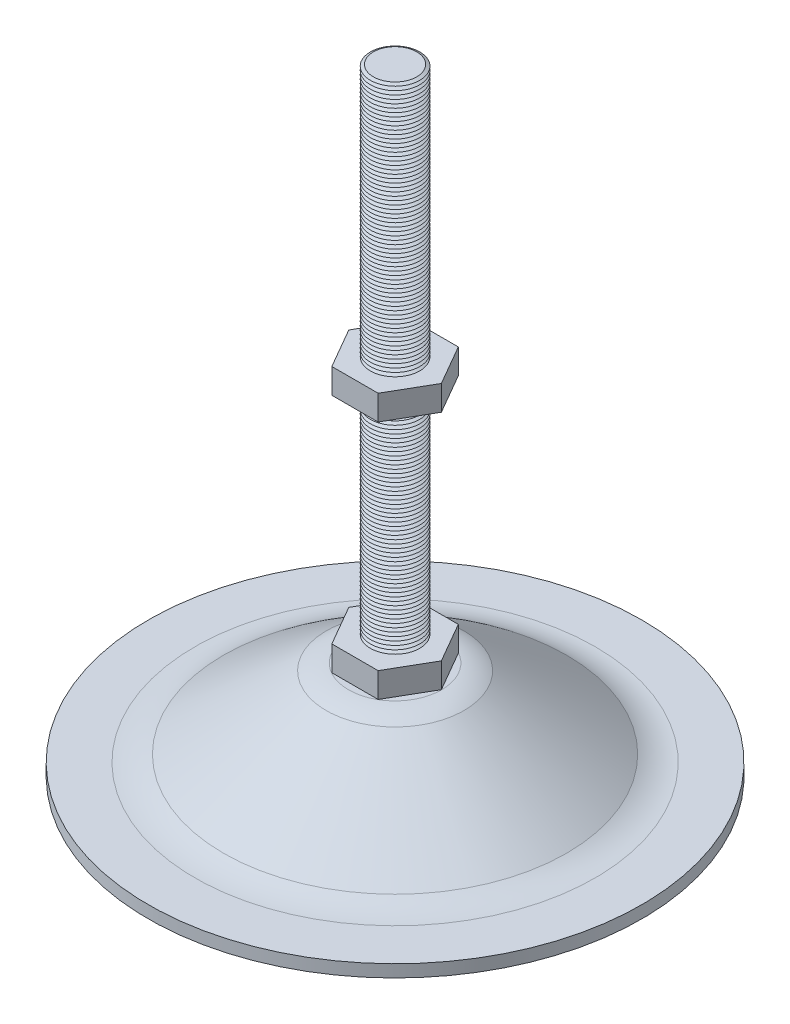
SolidWorks part; units mm, degrees
ref_plane "前视基准面" through (0, 0, 0) normal (0, 0, 1) x (1, 0, 0)
ref_plane "上视基准面" through (0, 0, 0) normal (0, 1, 0) x (1, 0, 0)
ref_plane "右视基准面" through (0, 0, 0) normal (1, 0, 0) x (0, 0, -1)
sketch "草图1" plane through (0, 0, 0) normal (0, 0, 1) x (1, 0, 0)
  line B0 (40, -12) -> (40, -14)
  line B1 (40, -12) -> (32.4605, -12)
  line B2 (27.8204, -10.8583) -> (11.1796, 0.8583)
  line B3 (26.8924, -12.63) -> (10.2516, -0.9133)
  line B4 (6.5395, 0) -> (0, 0)
  line B5 (32.4605, -14) -> (40, -14)
  line B6 (0, 0) -> (0, 86)
  line B7 (7.5, 1.9538) -> (7.5, 6)
  line B8 (4, 6) -> (7.5, 6)
  line B9 (3.5128, 86) -> (0, 86)
  line B10 (7.5, 40.9032) -> (7.5, 44.9495)
  line B11 (3.9956, 44.9495) -> (7.5, 44.9495)
  line B12 (7.5, 40.9032) -> (3.4497, 40.9032)
  line B13 (4, 6) -> (3.4, 6.3091)
  line B14 (4, 6.6182) -> (3.4, 6.3091)
  line B15 (4, 6.6182) -> (3.4, 6.9273)
  line B16 (4, 7.2364) -> (3.4, 6.9273)
  line B17 (4, 7.2364) -> (3.4, 7.5455)
  line B18 (4, 7.8546) -> (3.4, 7.5455)
  line B19 (4, 7.8546) -> (3.4, 8.1637)
  line B20 (4, 8.4728) -> (3.4, 8.1637)
  line B21 (4, 8.4728) -> (3.4, 8.7819)
  line B22 (4, 9.091) -> (3.4, 8.7819)
  line B23 (4, 9.091) -> (3.4, 9.4002)
  line B24 (4, 9.7093) -> (3.4, 9.4002)
  line B25 (4, 9.7093) -> (3.4, 10.0184)
  line B26 (4, 10.3275) -> (3.4, 10.0184)
  line B27 (4, 10.3275) -> (3.4, 10.6366)
  line B28 (4, 10.9457) -> (3.4, 10.6366)
  line B29 (4, 10.9457) -> (3.4, 11.2548)
  line B30 (4, 11.5639) -> (3.4, 11.2548)
  line B31 (4, 11.5639) -> (3.4, 11.873)
  line B32 (4, 12.1821) -> (3.4, 11.873)
  line B33 (4, 12.1821) -> (3.4, 12.4912)
  line B34 (4, 12.8003) -> (3.4, 12.4912)
  line B35 (4, 12.8003) -> (3.4, 13.1094)
  line B36 (4, 13.4185) -> (3.4, 13.1094)
  line B37 (4, 13.4185) -> (3.4, 13.7276)
  line B38 (4, 14.0367) -> (3.4, 13.7276)
  line B39 (4, 14.0367) -> (3.4, 14.3458)
  line B40 (4, 14.6549) -> (3.4, 14.3458)
  line B41 (4, 14.6549) -> (3.4, 14.964)
  line B42 (4, 15.2731) -> (3.4, 14.964)
  line B43 (4, 15.2731) -> (3.4, 15.5822)
  line B44 (4, 15.8913) -> (3.4, 15.5822)
  line B45 (4, 15.8913) -> (3.4, 16.2005)
  line B46 (4, 16.5096) -> (3.4, 16.2005)
  line B47 (4, 16.5096) -> (3.4, 16.8187)
  line B48 (4, 17.1278) -> (3.4, 16.8187)
  line B49 (4, 17.1278) -> (3.4, 17.4369)
  line B50 (4, 17.746) -> (3.4, 17.4369)
  line B51 (4, 17.746) -> (3.4, 18.0551)
  line B52 (4, 18.3642) -> (3.4, 18.0551)
  line B53 (4, 18.3642) -> (3.4, 18.6733)
  line B54 (4, 18.9824) -> (3.4, 18.6733)
  line B55 (4, 18.9824) -> (3.4, 19.2915)
  line B56 (4, 19.6006) -> (3.4, 19.2915)
  line B57 (4, 19.6006) -> (3.4, 19.9097)
  line B58 (4, 20.2188) -> (3.4, 19.9097)
  line B59 (4, 20.2188) -> (3.4, 20.5279)
  line B60 (4, 20.837) -> (3.4, 20.5279)
  line B61 (4, 20.837) -> (3.4, 21.1461)
  line B62 (4, 21.4552) -> (3.4, 21.1461)
  line B63 (4, 21.4552) -> (3.4, 21.7643)
  line B64 (4, 22.0734) -> (3.4, 21.7643)
  line B65 (4, 22.0734) -> (3.4, 22.3825)
  line B66 (4, 22.6916) -> (3.4, 22.3825)
  line B67 (4, 22.6916) -> (3.4, 23.0008)
  line B68 (4, 23.3099) -> (3.4, 23.0008)
  line B69 (4, 23.3099) -> (3.4, 23.619)
  line B70 (4, 23.9281) -> (3.4, 23.619)
  line B71 (4, 23.9281) -> (3.4, 24.2372)
  line B72 (4, 24.5463) -> (3.4, 24.2372)
  line B73 (4, 24.5463) -> (3.4, 24.8554)
  line B74 (4, 25.1645) -> (3.4, 24.8554)
  line B75 (4, 25.1645) -> (3.4, 25.4736)
  line B76 (4, 25.7827) -> (3.4, 25.4736)
  line B77 (4, 25.7827) -> (3.4, 26.0918)
  line B78 (4, 26.4009) -> (3.4, 26.0918)
  line B79 (4, 26.4009) -> (3.4, 26.71)
  line B80 (4, 27.0191) -> (3.4, 26.71)
  line B81 (4, 27.0191) -> (3.4, 27.3282)
  line B82 (4, 27.6373) -> (3.4, 27.3282)
  line B83 (4, 27.6373) -> (3.4, 27.9464)
  line B84 (4, 28.2555) -> (3.4, 27.9464)
  line B85 (4, 28.2555) -> (3.4, 28.5646)
  line B86 (4, 28.8737) -> (3.4, 28.5646)
  line B87 (4, 28.8737) -> (3.4, 29.1828)
  line B88 (4, 29.492) -> (3.4, 29.1828)
  line B89 (4, 29.492) -> (3.4, 29.8011)
  line B90 (4, 30.1102) -> (3.4, 29.8011)
  line B91 (4, 30.1102) -> (3.4, 30.4193)
  line B92 (4, 30.7284) -> (3.4, 30.4193)
  line B93 (4, 30.7284) -> (3.4, 31.0375)
  line B94 (4, 31.3466) -> (3.4, 31.0375)
  line B95 (4, 31.3466) -> (3.4, 31.6557)
  line B96 (4, 31.9648) -> (3.4, 31.6557)
  line B97 (4, 31.9648) -> (3.4, 32.2739)
  line B98 (4, 32.583) -> (3.4, 32.2739)
  line B99 (4, 32.583) -> (3.4, 32.8921)
  line B100 (4, 33.2012) -> (3.4, 32.8921)
  line B101 (4, 33.2012) -> (3.4, 33.5103)
  line B102 (4, 33.8194) -> (3.4, 33.5103)
  line B103 (4, 33.8194) -> (3.4, 34.1285)
  line B104 (4, 34.4376) -> (3.4, 34.1285)
  line B105 (4, 34.4376) -> (3.4, 34.7467)
  line B106 (4, 35.0558) -> (3.4, 34.7467)
  line B107 (4, 35.0558) -> (3.4, 35.3649)
  line B108 (4, 35.674) -> (3.4, 35.3649)
  line B109 (4, 35.674) -> (3.4, 35.9831)
  line B110 (4, 36.2923) -> (3.4, 35.9831)
  line B111 (4, 36.2923) -> (3.4, 36.6014)
  line B112 (4, 36.9105) -> (3.4, 36.6014)
  line B113 (4, 36.9105) -> (3.4, 37.2196)
  line B114 (4, 37.5287) -> (3.4, 37.2196)
  line B115 (4, 37.5287) -> (3.4, 37.8378)
  line B116 (4, 38.1469) -> (3.4, 37.8378)
  line B117 (4, 38.1469) -> (3.4, 38.456)
  line B118 (4, 38.7651) -> (3.4, 38.456)
  line B119 (4, 38.7651) -> (3.4, 39.0742)
  line B120 (4, 39.3833) -> (3.4, 39.0742)
  line B121 (4, 39.3833) -> (3.4, 39.6924)
  line B122 (4, 40.0015) -> (3.4, 39.6924)
  line B123 (4, 40.0015) -> (3.4, 40.3106)
  line B124 (4, 40.6197) -> (3.4, 40.3106)
  line B125 (4, 40.6197) -> (3.4497, 40.9032)
  line B126 (3.9956, 44.9495) -> (3.4, 45.2563)
  line B127 (4, 45.5654) -> (3.4, 45.2563)
  line B128 (4, 45.5654) -> (3.4, 45.8745)
  line B129 (4, 46.1836) -> (3.4, 45.8745)
  line B130 (4, 46.1836) -> (3.4, 46.4927)
  line B131 (4, 46.8018) -> (3.4, 46.4927)
  line B132 (4, 46.8018) -> (3.4, 47.1109)
  line B133 (4, 47.42) -> (3.4, 47.1109)
  line B134 (4, 47.42) -> (3.4, 47.7291)
  line B135 (4, 48.0382) -> (3.4, 47.7291)
  line B136 (4, 48.0382) -> (3.4, 48.3473)
  line B137 (4, 48.6564) -> (3.4, 48.3473)
  line B138 (4, 48.6564) -> (3.4, 48.9655)
  line B139 (4, 49.2746) -> (3.4, 48.9655)
  line B140 (4, 49.2746) -> (3.4, 49.5838)
  line B141 (4, 49.8929) -> (3.4, 49.5838)
  line B142 (4, 49.8929) -> (3.4, 50.202)
  line B143 (4, 50.5111) -> (3.4, 50.202)
  line B144 (4, 50.5111) -> (3.4, 50.8202)
  line B145 (4, 51.1293) -> (3.4, 50.8202)
  line B146 (4, 51.1293) -> (3.4, 51.4384)
  line B147 (4, 51.7475) -> (3.4, 51.4384)
  line B148 (4, 51.7475) -> (3.4, 52.0566)
  line B149 (4, 52.3657) -> (3.4, 52.0566)
  line B150 (4, 52.3657) -> (3.4, 52.6748)
  line B151 (4, 52.9839) -> (3.4, 52.6748)
  line B152 (4, 52.9839) -> (3.4, 53.293)
  line B153 (4, 53.6021) -> (3.4, 53.293)
  line B154 (4, 53.6021) -> (3.4, 53.9112)
  line B155 (4, 54.2203) -> (3.4, 53.9112)
  line B156 (4, 54.2203) -> (3.4, 54.5294)
  line B157 (4, 54.8385) -> (3.4, 54.5294)
  line B158 (4, 54.8385) -> (3.4, 55.1476)
  line B159 (4, 55.4567) -> (3.4, 55.1476)
  line B160 (4, 55.4567) -> (3.4, 55.7658)
  line B161 (4, 56.0749) -> (3.4, 55.7658)
  line B162 (4, 56.0749) -> (3.4, 56.3841)
  line B163 (4, 56.6932) -> (3.4, 56.3841)
  line B164 (4, 56.6932) -> (3.4, 57.0023)
  line B165 (4, 57.3114) -> (3.4, 57.0023)
  line B166 (4, 57.3114) -> (3.4, 57.6205)
  line B167 (4, 57.9296) -> (3.4, 57.6205)
  line B168 (4, 57.9296) -> (3.4, 58.2387)
  line B169 (4, 58.5478) -> (3.4, 58.2387)
  line B170 (4, 58.5478) -> (3.4, 58.8569)
  line B171 (4, 59.166) -> (3.4, 58.8569)
  line B172 (4, 59.166) -> (3.4, 59.4751)
  line B173 (4, 59.7842) -> (3.4, 59.4751)
  line B174 (4, 59.7842) -> (3.4, 60.0933)
  line B175 (4, 60.4024) -> (3.4, 60.0933)
  line B176 (4, 60.4024) -> (3.4, 60.7115)
  line B177 (4, 61.0206) -> (3.4, 60.7115)
  line B178 (4, 61.0206) -> (3.4, 61.3297)
  line B179 (4, 61.6388) -> (3.4, 61.3297)
  line B180 (4, 61.6388) -> (3.4, 61.9479)
  line B181 (4, 62.257) -> (3.4, 61.9479)
  line B182 (4, 62.257) -> (3.4, 62.5661)
  line B183 (4, 62.8752) -> (3.4, 62.5661)
  line B184 (4, 62.8752) -> (3.4, 63.1844)
  line B185 (4, 63.4935) -> (3.4, 63.1844)
  line B186 (4, 63.4935) -> (3.4, 63.8026)
  line B187 (4, 64.1117) -> (3.4, 63.8026)
  line B188 (4, 64.1117) -> (3.4, 64.4208)
  line B189 (4, 64.7299) -> (3.4, 64.4208)
  line B190 (4, 64.7299) -> (3.4, 65.039)
  line B191 (4, 65.3481) -> (3.4, 65.039)
  line B192 (4, 65.3481) -> (3.4, 65.6572)
  line B193 (4, 65.9663) -> (3.4, 65.6572)
  line B194 (4, 65.9663) -> (3.4, 66.2754)
  line B195 (4, 66.5845) -> (3.4, 66.2754)
  line B196 (4, 66.5845) -> (3.4, 66.8936)
  line B197 (4, 67.2027) -> (3.4, 66.8936)
  line B198 (4, 67.2027) -> (3.4, 67.5118)
  line B199 (4, 67.8209) -> (3.4, 67.5118)
  line B200 (4, 67.8209) -> (3.4, 68.13)
  line B201 (4, 68.4391) -> (3.4, 68.13)
  line B202 (4, 68.4391) -> (3.4, 68.7482)
  line B203 (4, 69.0573) -> (3.4, 68.7482)
  line B204 (4, 69.0573) -> (3.4, 69.3664)
  line B205 (4, 69.6756) -> (3.4, 69.3664)
  line B206 (4, 69.6756) -> (3.4, 69.9847)
  line B207 (4, 70.2938) -> (3.4, 69.9847)
  line B208 (4, 70.2938) -> (3.4, 70.6029)
  line B209 (4, 70.912) -> (3.4, 70.6029)
  line B210 (4, 70.912) -> (3.4, 71.2211)
  line B211 (4, 71.5302) -> (3.4, 71.2211)
  line B212 (4, 71.5302) -> (3.4, 71.8393)
  line B213 (4, 72.1484) -> (3.4, 71.8393)
  line B214 (4, 72.1484) -> (3.4, 72.4575)
  line B215 (4, 72.7666) -> (3.4, 72.4575)
  line B216 (4, 72.7666) -> (3.4, 73.0757)
  line B217 (4, 73.3848) -> (3.4, 73.0757)
  line B218 (4, 73.3848) -> (3.4, 73.6939)
  line B219 (4, 74.003) -> (3.4, 73.6939)
  line B220 (4, 74.003) -> (3.4, 74.3121)
  line B221 (4, 74.6212) -> (3.4, 74.3121)
  line B222 (4, 74.6212) -> (3.4, 74.9303)
  line B223 (4, 75.2394) -> (3.4, 74.9303)
  line B224 (4, 75.2394) -> (3.4, 75.5485)
  line B225 (4, 75.8576) -> (3.4, 75.5485)
  line B226 (4, 75.8576) -> (3.4, 76.1667)
  line B227 (4, 76.4759) -> (3.4, 76.1667)
  line B228 (4, 76.4759) -> (3.4, 76.785)
  line B229 (4, 77.0941) -> (3.4, 76.785)
  line B230 (4, 77.0941) -> (3.4, 77.4032)
  line B231 (4, 77.7123) -> (3.4, 77.4032)
  line B232 (4, 77.7123) -> (3.4, 78.0214)
  line B233 (4, 78.3305) -> (3.4, 78.0214)
  line B234 (4, 78.3305) -> (3.4, 78.6396)
  line B235 (4, 78.9487) -> (3.4, 78.6396)
  line B236 (4, 78.9487) -> (3.4, 79.2578)
  line B237 (4, 79.5669) -> (3.4, 79.2578)
  line B238 (4, 79.5669) -> (3.4, 79.876)
  line B239 (4, 80.1851) -> (3.4, 79.876)
  line B240 (4, 80.1851) -> (3.4, 80.4942)
  line B241 (4, 80.8033) -> (3.4, 80.4942)
  line B242 (4, 80.8033) -> (3.4, 81.1124)
  line B243 (4, 81.4215) -> (3.4, 81.1124)
  line B244 (4, 81.4215) -> (3.4, 81.7306)
  line B245 (4, 82.0397) -> (3.4, 81.7306)
  line B246 (4, 82.0397) -> (3.4, 82.3488)
  line B247 (4, 82.6579) -> (3.4, 82.3488)
  line B248 (4, 82.6579) -> (3.4, 82.967)
  line B249 (4, 83.2762) -> (3.4, 82.967)
  line B250 (4, 83.2762) -> (3.4, 83.5853)
  line B251 (4, 83.8944) -> (3.4, 83.5853)
  line B252 (4, 83.8944) -> (3.4, 84.2035)
  line B253 (4, 84.5126) -> (3.4, 84.2035)
  line B254 (4, 84.5126) -> (3.4, 84.8217)
  line B255 (4, 85.1308) -> (3.4, 84.8217)
  line B256 (4, 85.1308) -> (3.4, 85.4399)
  line B257 (4, 85.749) -> (3.4, 85.4399)
  line B258 (4, 85.749) -> (3.5128, 86)
  arc B259 (27.8204, -10.8583) -> (32.4605, -12) centre (32.4605, -2) ccw
  arc B260 (11.1796, 0.8583) -> (7.5, 1.9538) centre (6.5395, -8) ccw
  arc B261 (26.8924, -12.63) -> (32.4605, -14) centre (32.4605, -2) ccw
  arc B262 (10.2516, -0.9133) -> (6.5395, 0) centre (6.5395, -8) ccw
sketch_block_instance "A$C37827301-1"
sketch_block "A$C37827301"
revolve "旋转1" add sketch "草图1" angle 360 about L6
sketch "草图3" plane through (0, 44.9495, 0) normal (0, 1, 0) x (1, 0, 0)
  line L1 (7.5056, 0) -> (3.7528, 6.5)
  line L2 (3.7528, 6.5) -> (-3.7528, 6.5)
  line L3 (-3.7528, 6.5) -> (-7.5056, 0)
  line L4 (-7.5056, 0) -> (-3.7528, -6.5)
  line L5 (-3.7528, -6.5) -> (3.7528, -6.5)
  line L6 (3.7528, -6.5) -> (7.5056, 0)
  line L7 (-17.245, 14.713) -> (17.5683, 14.713)
  line L8 (-17.245, 14.713) -> (-17.245, -21.5715)
  line L9 (-17.245, -21.5715) -> (17.5683, -21.5715)
  line L10 (17.5683, 14.713) -> (17.5683, -21.5715)
  circle A0 centre (0, 0) radius 27.8204 construction
extrude "切除-拉伸1" cut sketch "草图3" against normal blind 43
